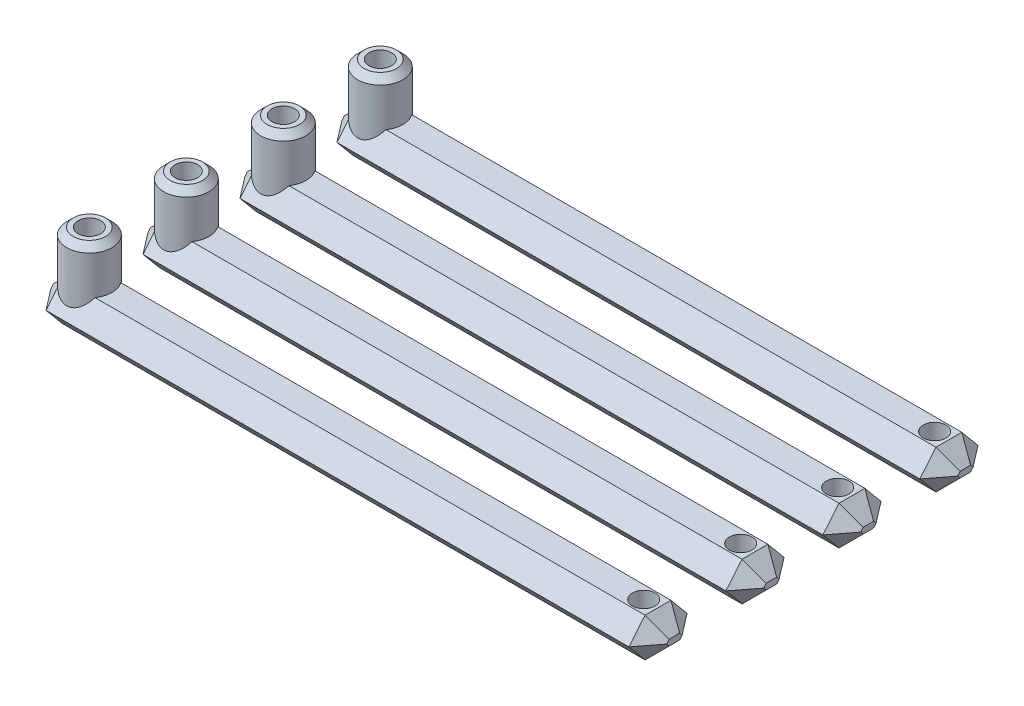
SolidWorks part; units mm, degrees
material "Plain Carbon Steel"
ref_plane "Front Plane" through (0, 0, 0) normal (0, 0, 1) x (1, 0, 0)
ref_plane "Top Plane" through (0, 0, 0) normal (0, 1, 0) x (1, 0, 0)
ref_plane "Right Plane" through (0, 0, 0) normal (1, 0, 0) x (0, 0, -1)
sketch "Sketch1" plane through (0, 0, 0) normal (1, 0, 0) x (0, 0, -1)
  line L0 (-2, -3) -> (-4.5, 0)
  line L1 (-2, -3) -> (2, -3)
  line L3 (-2, 3) -> (2, 3)
  line L5 (-2, -3) -> (2, 3) construction
  line L6 (-2, 3) -> (2, -3) construction
  line L7 (-4.5, 0) -> (-2, 3)
  line L8 (2, 3) -> (4.5, 0)
  line L9 (4.5, 0) -> (2, -3)
  point P0 (0, 0)
  dimension "D1" = 9
  dimension "D2" = 4
  dimension "D3" = 6
extrude "Boss-Extrude1" add sketch "Sketch1" along normal mid plane 95.25 contours L8 L9 L1 L0 L7 L3
sketch "Sketch2" plane through (0, -3, 0) normal (0, -1, 0) x (1, 0, 0)
  line L0 (47.625, 2) -> (47.625, -2) construction
  circle A0 centre (42.875, 0) radius 1.75
  point P2 (47.625, 0)
  dimension "D1" = 3.5
  dimension "D2" = 3
extrude "Cut-Extrude1" cut sketch "Sketch2" against normal up to surface (6 mm away) up to face at (0, 3, 0)
chamfer "Chamfer1" distance 2.54 angle 45 6 edges at (47.625, 1.5, -3.25) (47.625, -1.5, -3.25) (47.625, -3, 0) (47.625, -1.5, 3.25) (47.625, 1.5, 3.25) (47.625, 3, 0)
mirror "Mirror4" about plane through (0, 0, 0) normal (1, 0, 0) of "Cut-Extrude1"
chamfer "Chamfer2" distance 2.54 angle 45 6 edges at (-47.625, 1.5, 3.25) (-47.625, -1.5, 3.25) (-47.625, -3, 0) (-47.625, -1.5, -3.25) (-47.625, 1.5, -3.25) (-47.625, 3, 0)
sketch "Sketch3" plane through (0, 3, 0) normal (0, 1, 0) x (1, 0, 0)
  circle A0 centre (-42.875, 0) radius 3.5
  circle A1 centre (-42.875, 0) radius 1.75 construction
  circle A2 centre (-42.875, 0) radius 1.75
  dimension "D1" = 7
extrude "Boss-Extrude2" add sketch "Sketch3" along normal blind 7 and the other way up to next
chamfer "Chamfer3" distance 1 angle 45 1 edges at (-42.875, 10, 3.5)
pattern_linear "LPattern1" count 4 spacing 15 along (0, 0, 1) of bodies 104
